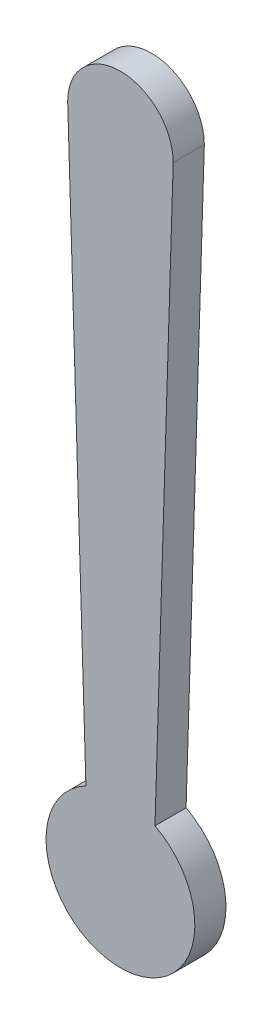
SolidWorks part; units mm, degrees
ref_plane "前视基准面" through (0, 0, 0) normal (0, 0, 1) x (1, 0, 0)
ref_plane "上视基准面" through (0, 0, 0) normal (0, 1, 0) x (1, 0, 0)
ref_plane "右视基准面" through (0, 0, 0) normal (1, 0, 0) x (0, 0, -1)
sketch "草图1" plane through (0, 0, 0) normal (0, 0, 1) x (1, 0, 0)
  line L0 (0, -120) -> (0, 120)
  line L1 (-19.5, 120) -> (-12, -120)
  line L2 (19.5, 120) -> (12, -120)
  circle A0 centre (0, 120) radius 19.5
  circle A1 centre (0, -120) radius 12
  circle A2 centre (0, -120) radius 27.5
  point P4 (0, 0)
  dimension "D1" = 39
  dimension "D2" = 24
  dimension "D3" = 55
  dimension "D4" = 240
extrude "凸台-拉伸1" add sketch "草图1" along normal blind 11.5
